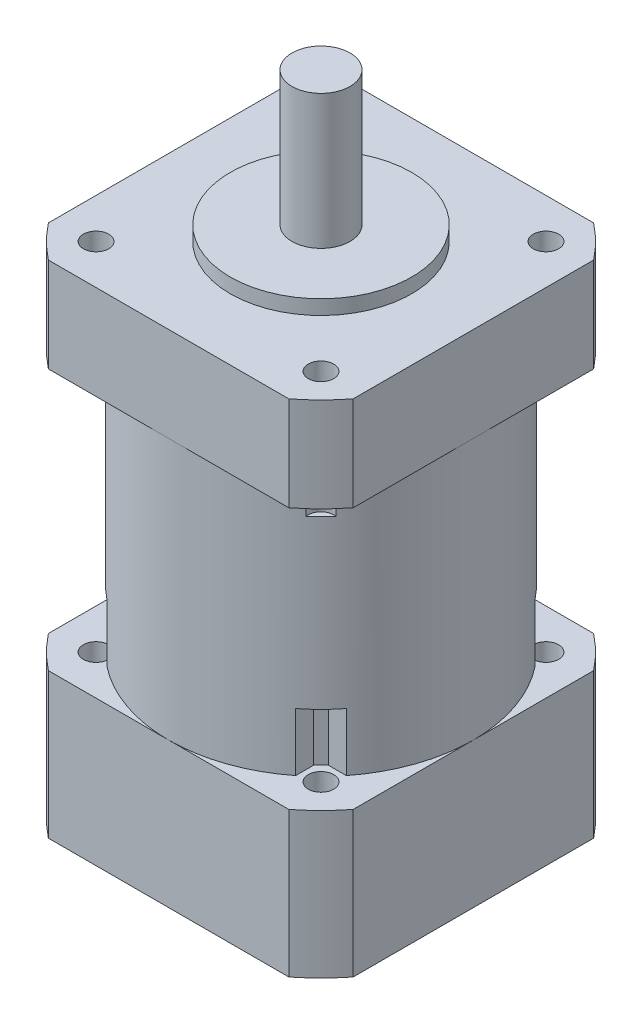
SolidWorks part; units mm, degrees
ref_plane "前视基准面" through (0, 0, 0) normal (0, 0, 1) x (1, 0, 0)
ref_plane "上视基准面" through (0, 0, 0) normal (0, 1, 0) x (1, 0, 0)
ref_plane "右视基准面" through (0, 0, 0) normal (1, 0, 0) x (0, 0, -1)
sketch "草图1" plane through (0, 0, 0) normal (0, 1, 0) x (1, 0, 0)
  line L1 (-21, 21) -> (21, 21)
  line L2 (-21, 21) -> (-21, -21)
  line L3 (-21, -21) -> (21, -21)
  line L4 (21, 21) -> (21, -21)
  line L5 (-21, 21) -> (21, -21) construction
  line L6 (-21, -21) -> (21, 21) construction
  circle A0 centre (0, 0) radius 26.75
  point P0 (0, 0)
  dimension "D3" = 53.5
  dimension "D1" = 42
  dimension "D2" = 42
extrude "凸台-拉伸1" add sketch "草图1" along normal blind 20 contours L3 A0 L4 L1 L2
sketch "草图2" plane through (0, 20, 0) normal (0, 1, 0) x (1, 0, 0)
  circle A0 centre (0, 0) radius 21
  dimension "D1" = 42
extrude "凸台-拉伸2" add sketch "草图2" along normal blind 49
sketch "草图3" plane through (0, 69, 0) normal (0, 1, 0) x (1, 0, 0)
  circle A0 centre (0, 0) radius 12.5
  dimension "D1" = 25
extrude "凸台-拉伸3" add sketch "草图3" along normal blind 2
sketch "草图4" plane through (0, 71, 0) normal (0, 1, 0) x (1, 0, 0)
  circle A0 centre (0, 0) radius 4
  dimension "D1" = 8
extrude "凸台-拉伸4" add sketch "草图4" along normal blind 18.5
sketch "草图5" plane through (0, 0, 0) normal (0, -1, 0) x (1, 0, 0)
  line L1 (-15.5, 15.5) -> (15.5, 15.5) construction
  line L2 (-15.5, 15.5) -> (-15.5, -15.5) construction
  line L3 (-15.5, -15.5) -> (15.5, -15.5) construction
  line L4 (15.5, 15.5) -> (15.5, -15.5) construction
  line L5 (-15.5, 15.5) -> (15.5, -15.5) construction
  line L6 (-15.5, -15.5) -> (15.5, 15.5) construction
  circle A0 centre (15.5, 15.5) radius 1.75
  circle A1 centre (15.5, -15.5) radius 1.75
  circle A2 centre (-15.5, -15.5) radius 1.75
  circle A3 centre (-15.5, 15.5) radius 1.75
  point P0 (0, 0)
  point P16 (0, 0)
  dimension "D3" = 3.5
  dimension "D1" = 31
  dimension "D2" = 31
  dimension "D4" = 4
extrude "切除-拉伸1" cut sketch "草图5" against normal blind 22.5
sketch "草图6" plane through (0, 20, 0) normal (0, 1, 0) x (1, 0, 0)
  line L0 (-13, -13) -> (-18, -13)
  line L1 (13, -13) -> (18, -13)
  line L2 (13, -13) -> (13, -18)
  line L3 (13, -18) -> (18, -18)
  line L4 (18, -13) -> (18, -18)
  line L5 (13, -13) -> (18, -18) construction
  line L6 (13, -18) -> (18, -13) construction
  line L7 (-13, -13) -> (-13, -18)
  line L8 (-13, -18) -> (-18, -18)
  line L9 (-18, -13) -> (-18, -18)
  line L10 (-13, 13) -> (-13, 18)
  line L11 (-13, 13) -> (-18, 13)
  line L12 (-18, 13) -> (-18, 18)
  line L13 (-13, 18) -> (-18, 18)
  line L14 (13, 13) -> (18, 13)
  line L15 (13, 13) -> (13, 18)
  line L16 (13, 18) -> (18, 18)
  line L17 (18, 13) -> (18, 18)
  point P0 (15.5, -15.5)
  point P21 (0, 0)
  dimension "D1" = 5
  dimension "D2" = 5
  dimension "D3" = 4
extrude "切除-拉伸2" cut sketch "草图6" along normal blind 8
chamfer "倒角1" distance 1 angle 45 4 edges at (13, 24, -13) (-13, 24, -13) (-13, 24, 13) (13, 24, 13)
sketch "草图7" plane through (0, 0, 0) normal (0, -1, 0) x (1, 0, 0)
  circle A0 centre (0, 0) radius 12
  dimension "D1" = 24
extrude "切除-拉伸3" cut sketch "草图7" against normal blind 23
sketch "草图8" plane through (0, 23, 0) normal (0, -1, 0) x (1, 0, 0)
  line L0 (-0.5, 2.0396) -> (-0.5, 10.9886)
  line L1 (0, 0) -> (0, 1.526) construction
  line L2 (0.5, 2.0396) -> (0.5, 10.9886)
  circle A0 centre (0, 0) radius 11
  circle A1 centre (0, 0) radius 2.1
  dimension "D1" = 22
  dimension "D2" = 4.2
  dimension "D3" = 1
extrude "凸台-拉伸5" add sketch "草图8" along normal blind 20 contours A1 L0 A0 L2
sketch "草图9" plane through (0, 69, 0) normal (0, 1, 0) x (1, 0, 0)
  line L4 (-16.5699, -21) -> (16.5699, -21)
  line L5 (-21, 16.5699) -> (-21, -16.5699)
  line L6 (16.5699, 21) -> (-16.5699, 21)
  line L7 (21, -16.5699) -> (21, 16.5699)
  line L8 (-16.5699, -21) -> (16.5699, -21)
  line L9 (-21, 16.5699) -> (-21, -16.5699)
  line L10 (16.5699, 21) -> (-16.5699, 21)
  line L11 (21, -16.5699) -> (21, 16.5699)
  circle A1 centre (15.5, 15.5) radius 1.75
  circle A2 centre (15.5, 15.5) radius 1.75
  circle A3 centre (15.5, -15.5) radius 1.75
  circle A4 centre (15.5, -15.5) radius 1.75
  circle A5 centre (-15.5, 15.5) radius 1.75
  circle A6 centre (-15.5, 15.5) radius 1.75
  circle A7 centre (-15.5, -15.5) radius 1.75
  circle A8 centre (-15.5, -15.5) radius 1.75
  circle A9 centre (0, 0) radius 12
  circle A10 centre (0, 0) radius 12
  arc A14 (-21, -16.5699) -> (-16.5699, -21) centre (0, 0) ccw
  arc A15 (-16.5699, 21) -> (-21, 16.5699) centre (0, 0) ccw
  arc A16 (21, 16.5699) -> (16.5699, 21) centre (0, 0) ccw
  arc A17 (16.5699, -21) -> (21, -16.5699) centre (0, 0) ccw
  arc A18 (-21, -16.5699) -> (-16.5699, -21) centre (0, 0) ccw
  arc A19 (-16.5699, 21) -> (-21, 16.5699) centre (0, 0) ccw
  arc A20 (21, 16.5699) -> (16.5699, 21) centre (0, 0) ccw
  arc A21 (16.5699, -21) -> (21, -16.5699) centre (0, 0) ccw
  dimension "D1" = 0
  dimension "D2" = 0
  dimension "D3" = 0
  dimension "D4" = 0
  dimension "D5" = 0
  dimension "D6" = 0
extrude "凸台-拉伸6" add sketch "草图9" against normal blind 13
sketch "草图10" plane through (0, 69, 0) normal (0, 1, 0) x (1, 0, 0)
  circle A1 centre (15.5, -15.5) radius 1.75
  circle A2 centre (15.5, -15.5) radius 1.75
  circle A3 centre (-15.5, -15.5) radius 1.75
  circle A4 centre (-15.5, -15.5) radius 1.75
  circle A5 centre (-15.5, 15.5) radius 1.75
  circle A6 centre (-15.5, 15.5) radius 1.75
  circle A7 centre (15.5, 15.5) radius 1.75
  circle A8 centre (15.5, 15.5) radius 1.75
  dimension "D1" = 0
  dimension "D2" = 0
  dimension "D3" = 0
  dimension "D4" = 0
extrude "切除-拉伸4" cut sketch "草图10" against normal blind 18
